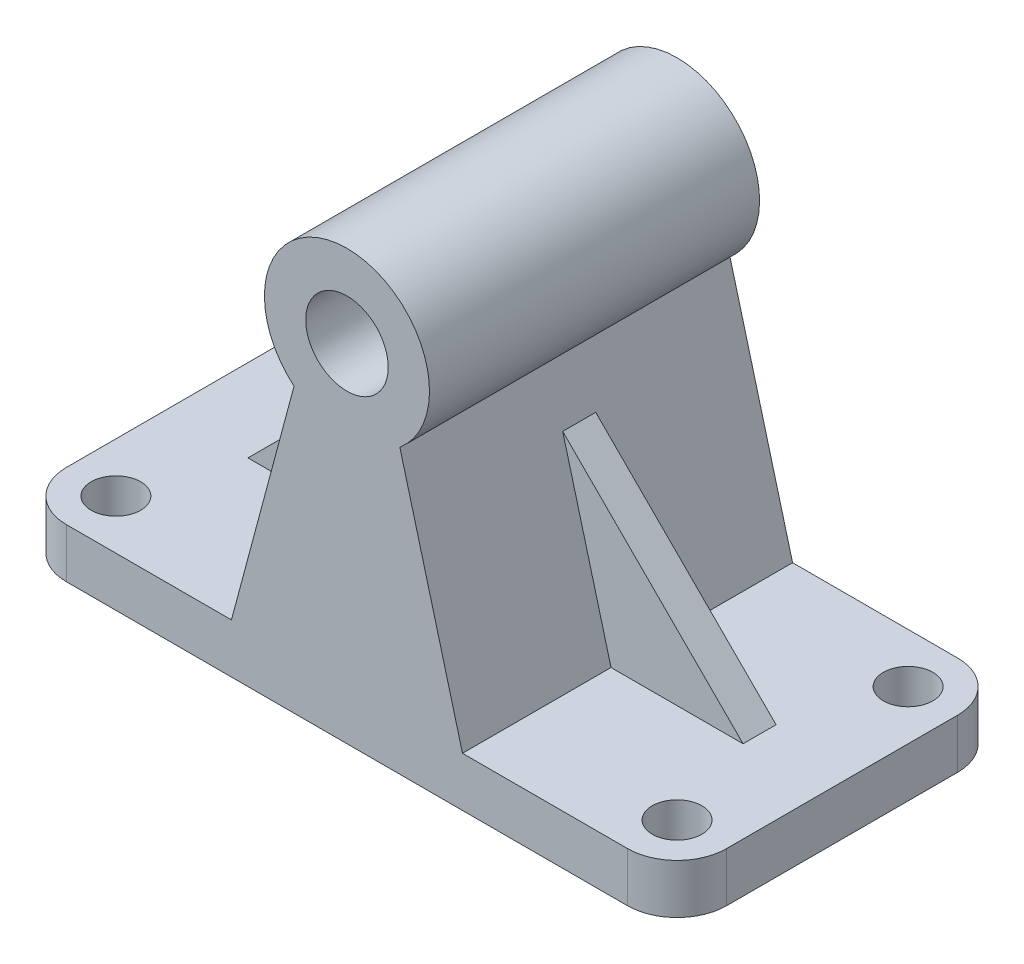
SolidWorks part; units mm, degrees
ref_plane "Front Plane" through (0, 0, 0) normal (0, 0, 1) x (1, 0, 0)
ref_plane "Top Plane" through (0, 0, 0) normal (0, 1, 0) x (1, 0, 0)
ref_plane "Right Plane" through (0, 0, 0) normal (1, 0, 0) x (0, 0, -1)
sketch "Sketch1" plane through (0, 0, 0) normal (0, 0, 1) x (1, 0, 0)
  line L0 (-35, 15) -> (-16.0259, 85.8122)
  line L1 (-100, 0) -> (100, 0)
  line L2 (-100, 0) -> (-100, 15)
  line L3 (-100, 15) -> (-35, 15)
  line L4 (100, 0) -> (100, 15)
  line L5 (0, -36.0099) -> (0, 166.6143) construction
  line L6 (16.0259, 85.8122) -> (35, 15)
  line L7 (35, 15) -> (100, 15)
  arc A0 (16.0259, 85.8122) -> (-16.0259, 85.8122) centre (0, 105) ccw
  circle A1 centre (0, 105) radius 12.5
  point P13 (0, 0)
  dimension "D6" = 25
  dimension "D7" = 25
  dimension "D1" = 200
  dimension "D2" = 15
  dimension "D3" = 70
  dimension "D4" = 75
  dimension "D5" = 90
extrude "Boss-Extrude1" add sketch "Sketch1" along normal mid plane 100
fillet "Fillet1" radius 15 4 edges at (-100, 7.5, 50) (-100, 7.5, -50) (100, 7.5, -50) (100, 7.5, 50)
sketch "Sketch2" plane through (0, 15, 0) normal (0, 1, 0) x (1, 0, 0)
  circle A0 centre (-85, 35) radius 7.5
  circle A1 centre (-85, -35) radius 7.5
  circle A2 centre (85, 35) radius 7.5
  circle A3 centre (85, -35) radius 7.5
  point P12 (0, 0)
  dimension "D1" = 15
extrude "Cut-Extrude1" cut sketch "Sketch2" against normal through all
sketch "Sketch3" plane through (0, 0, 0) normal (0, 0, 1) x (1, 0, 0)
  line L0 (75, 15) -> (20.359, 69.641)
  line L1 (85, 15) -> (35, 15) construction
  line L3 (35, 15) -> (16.0259, 85.8122) construction
  point P4 (24.0601, 55.8284)
  dimension "D1" = 40
  dimension "D2" = 45
rib "Rib1" sketch "Sketch3" sketch "Sketch3" thickness 10 extrusion direction parallel to sketch draft on no parameters "D1"=10
mirror "Mirror1" about plane through (0, 0, 0) normal (1, 0, 0) of "Rib1"
